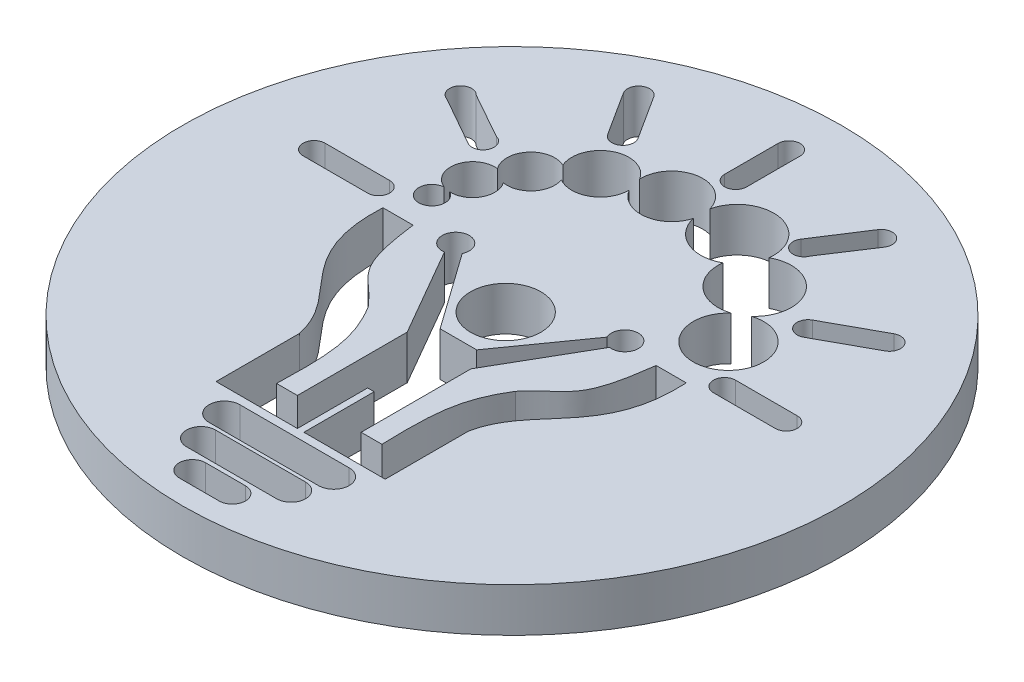
SolidWorks part; units mm, degrees
ref_plane "Front Plane" through (0, 0, 0) normal (0, 0, 1) x (1, 0, 0)
ref_plane "Top Plane" through (0, 0, 0) normal (0, 1, 0) x (1, 0, 0)
ref_plane "Right Plane" through (0, 0, 0) normal (1, 0, 0) x (0, 0, -1)
sketch "Sketch1" plane through (0, 0, 0) normal (0, 1, 0) x (1, 0, 0)
  line L0 (-25.4196, 99.7354) -> (195.2471, 99.7354) construction
  line L1 (-35.9524, 6.5793) -> (-29.0894, 6.5793)
  line L2 (-20.6779, -46.6665) -> (-2.1739, -46.6665)
  line L4 (-20.6779, -27.7184) -> (-20.6779, -46.6665)
  line L7 (-2.1739, -46.6665) -> (-2.1739, -30.679)
  line L8 (-13.4243, -40.1531) -> (-8.6873, -40.1531)
  line L9 (-8.6873, -40.1531) -> (-8.6873, -15.1531)
  line L10 (-8.6873, -15.1531) -> (-20.217, 4.8432)
  line L11 (2.7273, -10.7642) -> (-5.5929, -10.7642)
  line L12 (-5.5929, -10.7642) -> (-17.9016, 6.5717)
  line L13 (-2.1739, -30.679) -> (-1.4328, -30.679)
  line L14 (-1.4328, -30.679) -> (-1.4328, -10.7642) construction
  line L15 (17.8123, -27.7184) -> (17.8123, -46.6665)
  line L16 (-0.6917, -46.6665) -> (-0.6917, -30.679)
  line L17 (17.8123, -46.6665) -> (-0.6917, -46.6665)
  line L18 (10.5587, -40.1531) -> (5.8217, -40.1531)
  line L19 (5.8217, -40.1531) -> (5.8217, -15.1531)
  line L20 (2.7273, -10.7642) -> (15.036, 6.5717)
  line L21 (5.8217, -15.1531) -> (17.3514, 4.8432)
  line L22 (33.0868, 6.5793) -> (26.2238, 6.5793)
  line L23 (-31.1342, 56.4537) -> (-24.8148, 46.5863)
  line L24 (-26.9844, 59.2407) -> (-20.6046, 49.2832)
  line L25 (-13.4243, -48.5225) -> (11.4737, -48.5225)
  line L26 (-13.4243, -55.5225) -> (11.4737, -55.5225)
  line L27 (-11.2016, -56.2802) -> (9.3146, -56.2802)
  line L28 (-11.2016, -62.8802) -> (9.3146, -62.8802)
  line L29 (-5.8724, -63.8561) -> (3.1996, -63.8561)
  line L30 (-5.8724, -69.8561) -> (3.1996, -69.8561)
  line L31 (1.3322, 52.0688) -> (1.3322, 64.2244)
  line L32 (-3.6678, 64.2244) -> (-3.6678, 52.0688)
  line L33 (17.8123, 47.9841) -> (24.6878, 58.5981)
  line L34 (28.877, 55.8688) -> (22.2335, 45.7293)
  line L35 (-1.4328, -30.679) -> (-0.6917, -30.679)
  line L36 (38.137, 12.7217) -> (52.1931, 12.7217)
  line L37 (-47.5641, 39.4056) -> (-37.1443, 33.5639)
  line L38 (52.1931, 7.7217) -> (38.137, 7.7217)
  line L39 (-55.2648, 12.7217) -> (-40.5703, 12.7217)
  line L40 (-39.1189, 29.0572) -> (-50.1463, 35.3093)
  line L41 (-40.5703, 7.7217) -> (-55.2648, 7.7217)
  line L42 (35.0548, 33.3243) -> (47.0151, 39.8818)
  line L44 (49.4189, 35.4976) -> (37.4586, 28.94)
  arc A1 (-17.9016, 6.5717) -> (-20.217, 4.8432) centre (-20.6779, 7.8756) ccw
  circle A2 centre (-1.4328, 0) radius 8
  arc A3 (-33.0467, 17.6259) -> (-31.501, 17.3097) centre (-32.8539, 14.6321) ccw
  arc A4 (-31.501, 17.3097) -> (-27.163, 25.1958) centre (-31.2804, 22.3245) ccw
  arc A5 (-27.163, 25.1958) -> (-21.137, 32.3575) centre (-26.2607, 30.5527) ccw
  arc A6 (-21.137, 32.3575) -> (-11.4064, 38.0647) centre (-17.9112, 38.0064) ccw
  arc A7 (-11.4064, 38.0647) -> (1.4715, 39.795) centre (-5.3376, 41.6849) ccw
  arc A8 (1.4715, 39.795) -> (13.5949, 34.4079) centre (9.5699, 41.6849) ccw
  arc A9 (13.5949, 34.4079) -> (24.4277, 25.4394) centre (21.8637, 33.3689) ccw
  arc A10 (24.4277, 25.4394) -> (27.3781, 27.1205) centre (29.7732, 19.4875) ccw
  arc A11 (15.036, 6.5717) -> (17.3514, 4.8432) centre (17.8123, 7.8756) cw
  arc A12 (-26.9844, 59.2407) -> (-31.1342, 56.4537) centre (-29.0894, 57.8921) ccw
  arc A13 (-24.8148, 46.5863) -> (-20.6046, 49.2832) centre (-22.7097, 47.9347) ccw
  arc A14 (-30.6112, 27.2994) -> (-33.0467, 17.6259) centre (-31.2804, 22.3245) ccw
  arc A15 (-23.8884, 35.4397) -> (-30.6112, 27.2994) centre (-26.2607, 30.5527) ccw
  arc A16 (-12.4006, 41.4632) -> (-23.8884, 35.4397) centre (-17.9112, 38.0064) ccw
  arc A17 (1.4715, 43.5747) -> (-12.4006, 41.4632) centre (-5.3376, 41.6849) ccw
  arc A18 (17.822, 40.6571) -> (1.4715, 43.5747) centre (9.5699, 41.6849) ccw
  arc A19 (27.3781, 27.1205) -> (17.822, 40.6571) centre (21.8637, 33.3689) ccw
  arc A20 (-13.4243, -48.5225) -> (-13.4243, -55.5225) centre (-13.4243, -52.0225) ccw
  arc A21 (11.4737, -55.5225) -> (11.4737, -48.5225) centre (11.4737, -52.0225) ccw
  arc A22 (-11.2016, -56.2802) -> (-11.2016, -62.8802) centre (-11.2016, -59.5802) ccw
  arc A24 (9.3146, -62.8802) -> (9.3146, -56.2802) centre (9.3146, -59.5802) ccw
  arc A25 (-5.8724, -63.8561) -> (-5.8724, -69.8561) centre (-5.8724, -66.8561) ccw
  arc A26 (3.1996, -69.8561) -> (3.1996, -63.8561) centre (3.1996, -66.8561) ccw
  arc A28 (-3.6678, 52.0688) -> (1.3322, 52.0688) centre (-1.1678, 52.0688) ccw
  arc A29 (1.3322, 64.2244) -> (-3.6678, 64.2244) centre (-1.1678, 64.2244) ccw
  arc A30 (17.8123, 47.9841) -> (22.2335, 45.7293) centre (19.885, 46.5863) ccw
  arc A31 (28.877, 55.8688) -> (24.6878, 58.5981) centre (26.786, 57.2389) ccw
  arc A32 (38.137, 12.7217) -> (38.137, 7.7217) centre (38.137, 10.2217) ccw
  arc A33 (52.1931, 7.7217) -> (52.1931, 12.7217) centre (52.1931, 10.2217) ccw
  arc A34 (-40.5703, 7.7217) -> (-40.5703, 12.7217) centre (-40.5703, 10.2217) ccw
  arc A35 (-55.2648, 12.7217) -> (-55.2648, 7.7217) centre (-55.2648, 10.2217) ccw
  arc A36 (-39.1189, 29.0572) -> (-37.1443, 33.5639) centre (-37.7244, 31.1322) ccw
  arc A37 (-47.5641, 39.4056) -> (-50.1463, 35.3093) centre (-49.3822, 37.6897) ccw
  arc A38 (35.0548, 33.3243) -> (37.4586, 28.94) centre (36.2567, 31.1322) ccw
  arc A39 (49.4189, 35.4976) -> (47.0151, 39.8818) centre (48.217, 37.6897) ccw
  spline S0 degree 3 poles (-29.0894, 6.5793) (-27.0256, -9.6721) (-24.298, -7.4196) (-18.1664, -14.5219) knots 0 0 0 0 1 1 1 1
  spline S1 degree 3 poles (-35.9524, 6.5793) (-37.0025, -13.7508) (-23.2684, -15.1357) (-20.6779, -27.7184) knots 0 0 0 0 1 1 1 1
  spline S2 degree 3 poles (-18.1664, -14.5219) (-13.4779, -22.0595) (-13.0543, -27.9418) (-13.4243, -40.1531) knots 0 0 0 0 1 1 1 1
  spline S3 degree 3 poles (15.3008, -14.5219) (10.6123, -22.0595) (10.1887, -27.9418) (10.5587, -40.1531) knots 0 0 0 0 1 1 1 1
  spline S4 degree 3 poles (26.2238, 6.5793) (24.16, -9.6721) (21.4324, -7.4196) (15.3008, -14.5219) knots 0 0 0 0 1 1 1 1
  spline S5 degree 3 poles (33.0868, 6.5793) (34.1369, -13.7508) (20.4028, -15.1357) (17.8123, -27.7184) knots 0 0 0 0 1 1 1 1
  point P0 (-29.0894, 6.5793)
sketch "Sketch2" plane through (0, 0, 0) normal (0, 1, 0) x (1, 0, 0)
  circle A0 centre (0, 0) radius 75
extrude "Boss-Extrude2" add sketch "Sketch2" along normal blind 10
extrude "Cut-Extrude2" cut sketch "Sketch1" along normal blind 10
